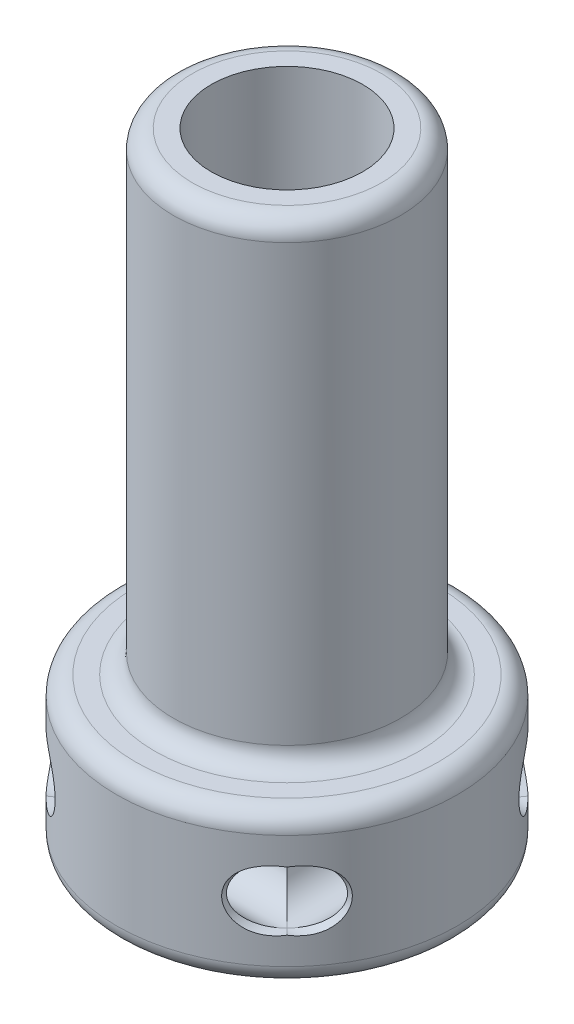
SolidWorks part; units mm, degrees
material "铜"
ref_plane "前视基准面" through (0, 0, 0) normal (0, 0, 1) x (1, 0, 0)
ref_plane "上视基准面" through (0, 0, 0) normal (0, 1, 0) x (1, 0, 0)
ref_plane "右视基准面" through (0, 0, 0) normal (1, 0, 0) x (0, 0, -1)
sketch "草图1" plane through (0, 0, 0) normal (0, 1, 0) x (1, 0, 0)
  circle A0 centre (0, 0) radius 6
  circle A1 centre (0, 0) radius 4
  dimension "D1" = 12
  dimension "D2" = 8
extrude "凸台-拉伸1" add sketch "草图1" along normal blind 30
sketch "草图2" plane through (0, 0, 0) normal (0, -1, 0) x (1, 0, 0)
  circle A0 centre (0, 0) radius 9
  dimension "D1" = 18
extrude "凸台-拉伸2" add sketch "草图2" along normal blind 3 and the other way blind 5
sketch "草图3" plane through (0, 0, 0) normal (1, 0, 0) x (0, 0, -1)
  circle A0 centre (-6, 1) radius 1.6
  circle A1 centre (6, 1) radius 1.6
  dimension "D1" = 3.2
  dimension "D2" = 3.2
  dimension "D3" = 6
  dimension "D4" = 6
  dimension "D5" = 1
  dimension "D6" = 1
extrude "切除-拉伸1" cut sketch "草图3" against normal through all and the other way through all
sketch "草图4" plane through (0, 0, 0) normal (0, 0, 1) x (1, 0, 0)
  circle A0 centre (-6, 1) radius 1.6
  circle A1 centre (6, 1) radius 1.6
  dimension "D1" = 3.2
  dimension "D2" = 3.2
  dimension "D3" = 6
  dimension "D4" = 6
  dimension "D5" = 1
  dimension "D6" = 1
extrude "切除-拉伸2" cut sketch "草图4" against normal through all and the other way through all
fillet "圆角1" radius 1 4 edges at (0, 5, -9) (0, 5, -6) (0, -3, -9) (0, 30, 6)
